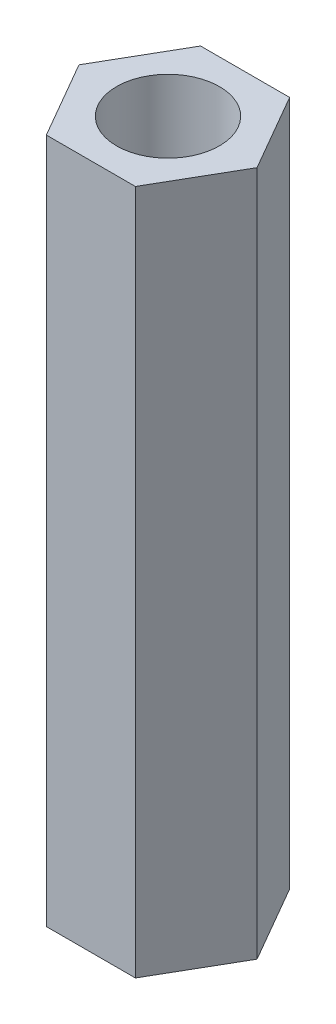
SolidWorks part; units mm, degrees
material "Commercial Bronze, UNS C22000 (90-10 Bronze)"
ref_plane "Front Plane" through (0, 0, 0) normal (0, 0, 1) x (1, 0, 0)
ref_plane "Top Plane" through (0, 0, 0) normal (0, 1, 0) x (1, 0, 0)
ref_plane "Right Plane" through (0, 0, 0) normal (1, 0, 0) x (0, 0, -1)
sketch "Sketch1" plane through (0, 0, 0) normal (0, 1, 0) x (1, 0, 0)
  line L1 (2.5981, 0) -> (1.299, 2.25)
  line L2 (1.299, 2.25) -> (-1.299, 2.25)
  line L3 (-1.299, 2.25) -> (-2.5981, 0)
  line L4 (-2.5981, 0) -> (-1.299, -2.25)
  line L5 (-1.299, -2.25) -> (1.299, -2.25)
  line L6 (1.299, -2.25) -> (2.5981, 0)
  circle A0 centre (0, 0) radius 2.25 construction
  circle A1 centre (0, 0) radius 1.5
  dimension "D1" = 4.5
  dimension "D2" = 3
extrude "Boss-Extrude1" add sketch "Sketch1" along normal blind 20
